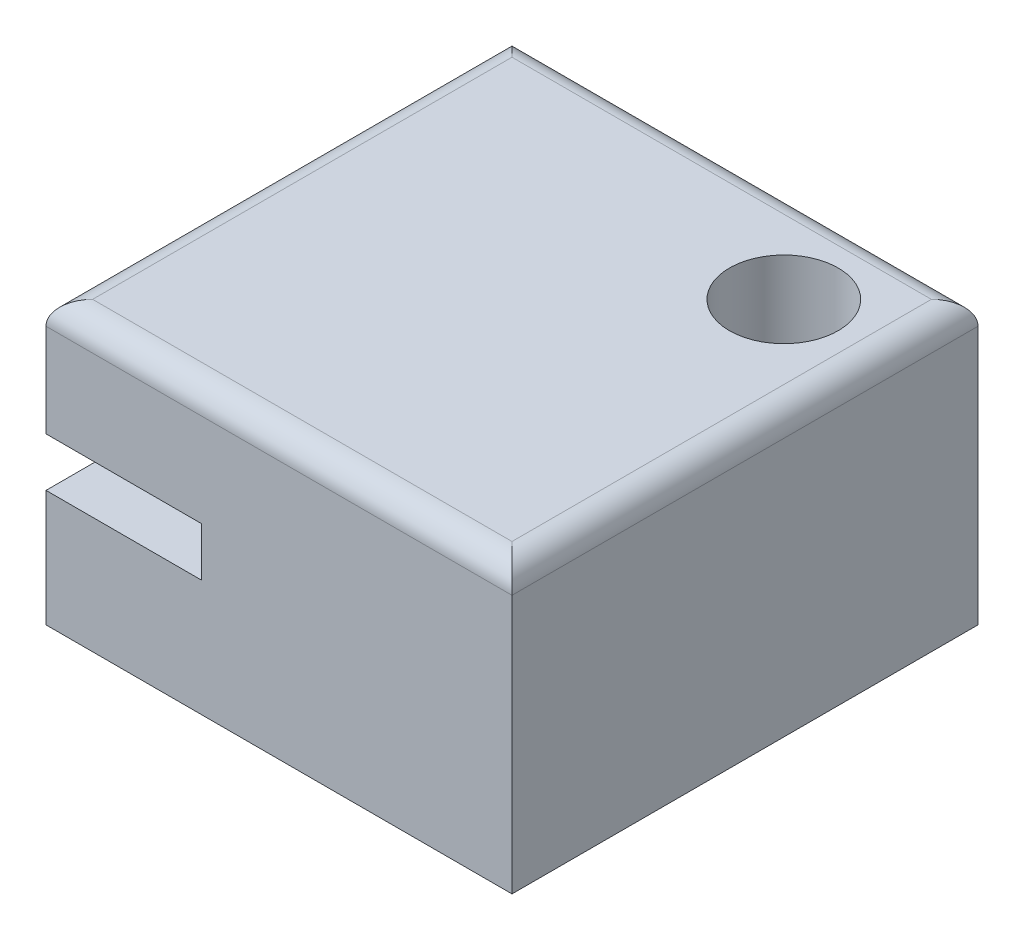
SolidWorks part; units mm, degrees
ref_plane "Front Plane" through (0, 0, 0) normal (0, 0, 1) x (1, 0, 0)
ref_plane "Top Plane" through (0, 0, 0) normal (0, 1, 0) x (1, 0, 0)
ref_plane "Right Plane" through (0, 0, 0) normal (1, 0, 0) x (0, 0, -1)
sketch "Sketch1" plane through (0, 0, 0) normal (0, 1, 0) x (1, 0, 0)
  line L1 (-8.802, -7.62) -> (6.438, -7.62)
  line L2 (-8.802, -7.62) -> (-8.802, 7.62)
  line L3 (-8.802, 7.62) -> (6.438, 7.62)
  line L4 (6.438, -7.62) -> (6.438, 7.62)
  line L5 (-8.802, -7.62) -> (6.438, 7.62) construction
  line L6 (-8.802, 7.62) -> (6.438, -7.62) construction
  point P0 (-1.182, 0)
  dimension "D1" = 15.24
  dimension "D2" = 15.24
extrude "Boss-Extrude1" add sketch "Sketch1" along normal blind 3.81
sketch "Sketch2" plane through (0, 3.81, 0) normal (0, 1, 0) x (1, 0, 0)
  line L0 (-8.802, 7.62) -> (-8.802, -7.62) construction
  line L5 (-8.802, -7.62) -> (-3.722, -7.62) construction
  line L6 (-8.802, -7.62) -> (-8.802, -2.54) construction
  line L7 (-8.802, -2.54) -> (-3.722, -2.54) construction
  line L8 (-3.722, -7.62) -> (-3.722, -2.54) construction
  line L9 (-8.802, -2.54) -> (-3.722, -2.54)
  line L10 (-3.722, -2.54) -> (-3.722, -7.62)
  line L11 (-3.722, -7.62) -> (6.438, -7.62)
  line L12 (6.438, -7.62) -> (6.438, 7.62)
  line L13 (-8.802, 7.62) -> (6.438, 7.62)
  line L14 (-8.802, 7.62) -> (-8.802, -2.54)
  dimension "D1" = 5.08
  dimension "D2" = 5.08
extrude "Boss-Extrude2" add sketch "Sketch2" along normal blind 1.6002
sketch "Sketch3" plane through (0, 5.4102, 0) normal (0, 1, 0) x (1, 0, 0)
  line L1 (-8.802, -7.62) -> (6.438, -7.62)
  line L2 (-8.802, -7.62) -> (-8.802, 7.62)
  line L3 (-8.802, 7.62) -> (6.438, 7.62)
  line L4 (6.438, -7.62) -> (6.438, 7.62)
extrude "Boss-Extrude3" add sketch "Sketch3" along normal blind 3.81
sketch "Sketch4" plane through (0, 9.2202, 0) normal (0, 1, 0) x (1, 0, 0)
  line L0 (6.438, -7.62) -> (6.438, 7.62) construction
  line L1 (6.438, 7.62) -> (-8.802, 7.62) construction
  circle A0 centre (3.263, 4.445) radius 1.778
  dimension "D1" = 3.556
  dimension "D2" = 3.175
  dimension "D3" = 3.175
extrude "Cut-Extrude1" cut sketch "Sketch4" against normal through all
fillet "Fillet1" radius 0.762 4 edges at (-1.182, 9.2202, -7.62) (6.438, 9.2202, 0) (-1.182, 9.2202, 7.62) (-8.802, 9.2202, 0)
